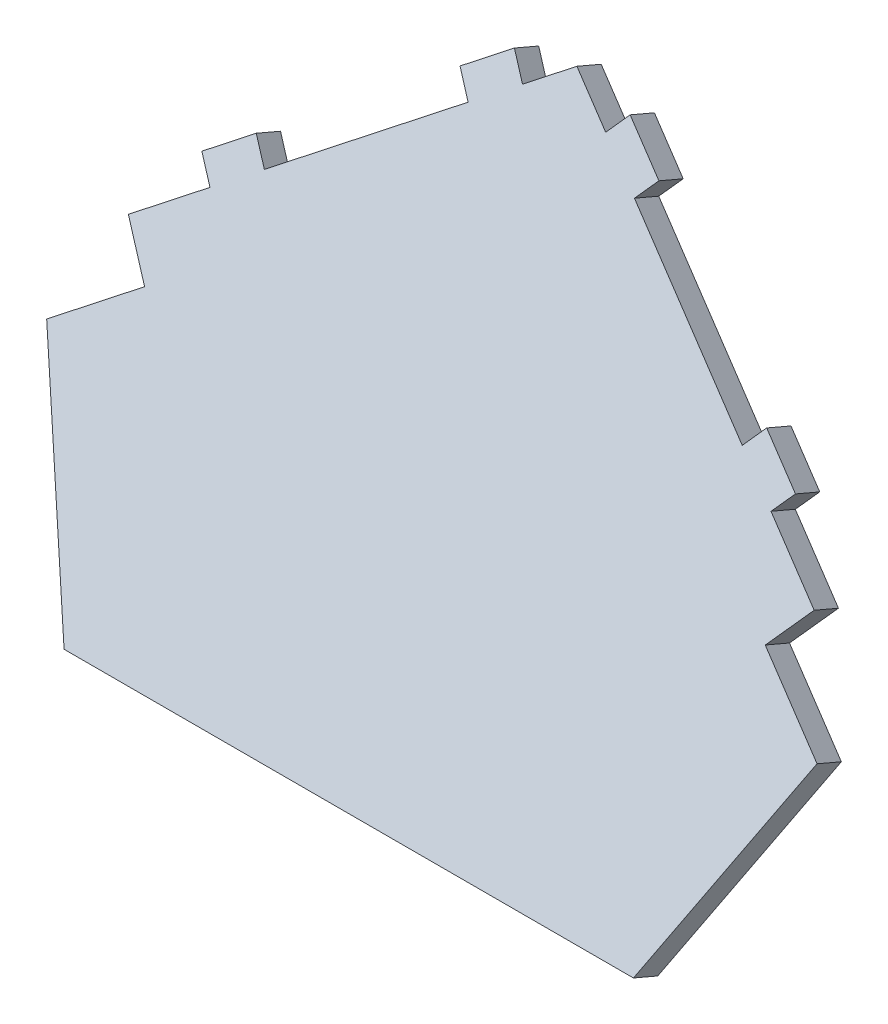
SolidWorks part; units mm, degrees
ref_plane "Plan de face" through (0, 0, 0) normal (0, 0, 1) x (1, 0, 0)
ref_plane "Plan de dessus" through (0, 0, 0) normal (0, 1, 0) x (1, 0, 0)
ref_plane "Plan de droite" through (0, 0, 0) normal (1, 0, 0) x (0, 0, -1)
sketch3d "Esquisse3D1"
  line L0 (0, 0, 0) -> (-64.9259, -46.74, 0) construction
  line L1 (-64.9259, -46.74, 0) -> (64.9259, -46.74, 0) construction
  line L2 (64.9259, -46.74, 0) -> (0, 0, 0) construction
  line L3 (0, 0, 0) -> (0, -46.74, 0) construction
  line L4 (0, 0, 0) -> (0, 0, -20) construction
  line L5 (0, 0, -20) -> (-7.8734, -5.6681, -17.5746)
  line L6 (0, 0, -20) -> (7.8734, -5.6681, -17.5746)
  line L7 (-64.9259, -46.74, 0) -> (-50, -66.74, 0) construction
  line L8 (-50, -66.74, 0) -> (50, -66.74, 0) construction
  line L9 (50, -66.74, 0) -> (64.9259, -46.74, 0) construction
  line L10 (0, -46.74, 0) -> (0, -66.74, 0) construction
  line L11 (0, 0, -20) -> (0, -15.7095, -56.7131) construction
  line L12 (64.9259, -46.74, 0) -> (58.7608, -53.9786, 3.0974)
  line L13 (58.7608, -53.9786, 3.0974) -> (72.9329, -64.1811, 7.463)
  line L14 (72.9329, -64.1811, 7.463) -> (-72.9329, -64.1811, 7.463) construction
  line L15 (-64.9259, -46.74, 0) -> (-58.7608, -53.9786, 3.0974)
  line L16 (-58.7608, -53.9786, 3.0974) -> (-72.9329, -64.1811, 7.463)
  line L17 (53.1158, -38.2379, -3.638) -> (56.1984, -34.6186, -5.1867)
  line L18 (48.3249, -28.9505, -7.6121) -> (56.1984, -34.6186, -5.1867)
  line L19 (48.3249, -28.9505, -7.6121) -> (45.2424, -32.5698, -6.0634)
  line L20 (53.1158, -38.2379, -3.638) -> (64.9259, -46.74, 0)
  line L21 (15.7468, -11.3361, -15.1493) -> (18.8294, -7.7168, -16.698)
  line L22 (18.8294, -7.7168, -16.698) -> (10.956, -2.0488, -19.1233)
  line L23 (10.956, -2.0488, -19.1233) -> (7.8734, -5.6681, -17.5746)
  line L24 (15.7468, -11.3361, -15.1493) -> (45.2424, -32.5698, -6.0634)
  line L25 (-7.8734, -5.6681, -17.5746) -> (-10.956, -2.0488, -19.1233)
  line L26 (-10.956, -2.0488, -19.1233) -> (-18.8294, -7.7168, -16.698)
  line L27 (-18.8294, -7.7168, -16.698) -> (-15.7468, -11.3361, -15.1493)
  line L28 (-53.1158, -38.2379, -3.638) -> (-56.1984, -34.6186, -5.1867)
  line L29 (-48.3249, -28.9505, -7.6121) -> (-56.1984, -34.6186, -5.1867)
  line L30 (-48.3249, -28.9505, -7.6121) -> (-45.2424, -32.5698, -6.0634)
  line L31 (-53.1158, -38.2379, -3.638) -> (-64.9259, -46.74, 0)
  line L32 (-15.7468, -11.3361, -15.1493) -> (-45.2424, -32.5698, -6.0634)
  line L33 (-72.9329, -64.1811, 7.463) -> (-53.9034, -100.9558, 23.1989)
  line L34 (-53.9034, -100.9558, 23.1989) -> (53.9034, -100.9558, 23.1989)
  line L35 (53.9034, -100.9558, 23.1989) -> (72.9329, -64.1811, 7.463)
  line L36 (0, -64.1811, 7.463) -> (0, -64.1811, 12.463) construction
  dimension "D1" = 108.5
  dimension "D2" = 20
  dimension "D3" = 80
  dimension "D4" = 100
  dimension "D5" = 20
  dimension "D6" = 102.62
  dimension "D14" = 18
  dimension "D7" = 10
  dimension "D8" = 10
  dimension "D9" = 5
  dimension "D10" = 15
  dimension "D11" = 10
  dimension "D12" = 10
  dimension "D13" = 5
  dimension "D15" = 40
extrude "Boss.-Extru.2" add sketch "Esquisse3D1" along direction (0, -0.3934, -0.9194) on the side of the normal blind 5
